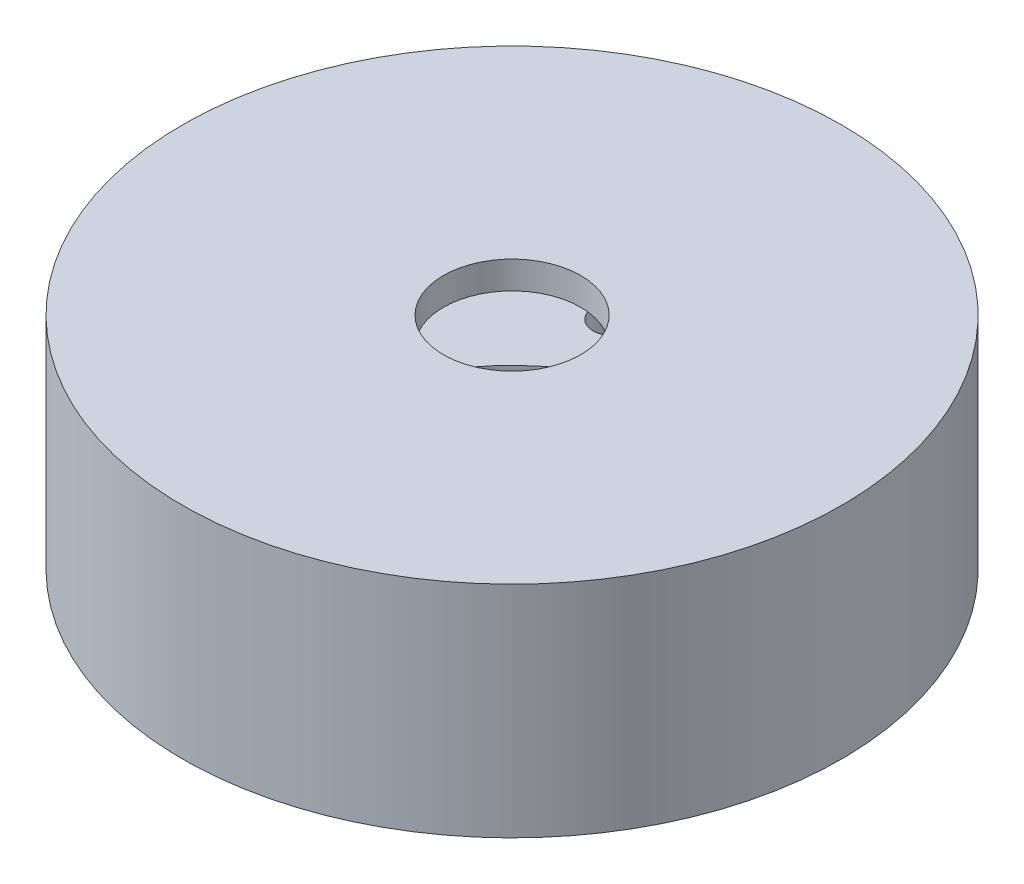
SolidWorks part; units mm, degrees
ref_plane "Front Plane" through (0, 0, 0) normal (0, 0, 1) x (1, 0, 0)
ref_plane "Top Plane" through (0, 0, 0) normal (0, 1, 0) x (1, 0, 0)
ref_plane "Right Plane" through (0, 0, 0) normal (1, 0, 0) x (0, 0, -1)
sketch "Sketch1" plane through (0, 0, 0) normal (0, 0, 1) x (1, 0, 0)
  line L0 (0, 50.8) -> (0, 142.2353) construction
  line L5 (-139.7, 0) -> (-152.4, 0)
  line L6 (-139.7, 0) -> (-139.7, 101.6)
  line L7 (-139.7, 101.6) -> (-152.4, 101.6)
  line L8 (-152.4, 0) -> (-152.4, 101.6)
  line L9 (-139.7, 0) -> (0, 0)
  line L10 (-139.7, 0) -> (-139.7, 12.7)
  line L11 (-139.7, 12.7) -> (0, 12.7)
  line L12 (0, 0) -> (0, 12.7)
  line L14 (-139.7, 101.6) -> (-31.75, 101.6)
  line L15 (-139.7, 101.6) -> (-139.7, 88.8554)
  line L16 (-139.7, 88.8554) -> (-31.75, 88.8554)
  line L17 (-31.75, 101.6) -> (-31.75, 88.8554)
  point P13 (-31.75, 95.2277)
  dimension "D1" = 31.75
  dimension "D3" = 12.7
  dimension "D4" = 12.7
revolve "Revolve1" add sketch "Sketch1" angle 360 about L0
sketch "Sketch5" plane through (0, 0, 0) normal (0, -1, 0) x (1, 0, 0)
  circle A0 centre (0, 0) radius 97.2481
  circle A1 centre (127.6751, 0) radius 9.2672
  circle A2 centre (63.8375, -110.5698) radius 9.2672
  circle A3 centre (-63.8375, -110.5698) radius 9.2672
  circle A4 centre (-127.6751, 0) radius 9.2672
  circle A5 centre (-63.8375, 110.5698) radius 9.2672
  circle A6 centre (63.8375, 110.5698) radius 9.2672
  point P17 (0, 0)
  dimension "D1" = 6
extrude "Cut-Extrude3" cut sketch "Sketch5" against normal up to next
sketch "Sketch3" plane through (0, 0, 0) normal (0, -1, 0) x (1, 0, 0)
  circle A0 centre (0, 0) radius 76.2
sketch "Sketch4" plane through (0, 0, 0) normal (1, 0, 0) x (0, 0, -1)
  line L0 (152.4, 0) -> (152.4, 101.6) construction
  line L1 (152.4, 50.8) -> (139.7, 50.8)
  line L2 (152.4, 50.8) -> (152.4, 81.116)
  line L3 (152.4, 81.116) -> (139.7, 81.116)
  line L4 (139.7, 50.8) -> (139.7, 81.116)
  dimension "D1" = 12.7
